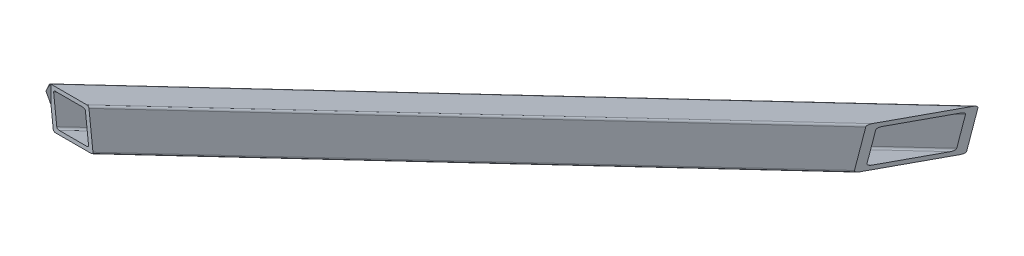
SolidWorks part; units mm, degrees
ref_plane "Plan de face" through (0, 0, 0) normal (0, 0, 1) x (1, 0, 0)
ref_plane "Plan de dessus" through (0, 0, 0) normal (0, 1, 0) x (1, 0, 0)
ref_plane "Plan de droite" through (0, 0, 0) normal (1, 0, 0) x (0, 0, -1)
sketch "Esquisse1" plane through (0, 0, 0) normal (0, 0, 1) x (1, 0, 0)
  line L0 (0, 0) -> (258, 0)
  line L1 (258, 0) -> (0, 256)
  line L2 (0, 256) -> (0, 0)
  dimension "D1" = 258
  dimension "D2" = 256
extrude "Boss.-Extru.1" add sketch "Esquisse1" along normal blind 729
sketch "Esquisse2" plane through (0, 0, 0) normal (-1, 0, 0) x (0, 0, 1)
  line L0 (0, 256) -> (729, 0)
  line L1 (729, 256) -> (0, 256) construction
  line L2 (0, 256) -> (0, 0) construction
  line L3 (729, 0) -> (729, 256)
  line L4 (729, 256) -> (0, 256)
extrude "Enlèv. mat.-Extru.1" cut sketch "Esquisse2" against normal blind 727
ref_plane "Plan1" through (0, 256, 0) normal (0.3167, -0.3143, 0.8949) x (0.9485, 0.1052, -0.2987)
sketch "Esquisse3" plane through (0, 256, 0) normal (0.3167, -0.3143, 0.8949) x (0.9485, 0.1052, -0.2987)
  line L1 (0, 0) -> (40, 0)
  line L2 (0, 0) -> (0, -40)
  line L3 (0, -40) -> (40, -40)
  line L4 (40, 0) -> (40, -40)
  dimension "D1" = 40
  dimension "D2" = 40
extrude "Boss.-Extru.2" add sketch "Esquisse3" along normal up to vertex (814.5803 mm away) up to point (258, 0, 729)
sketch "Esquisse4" plane through (0, 0, 0) normal (0, -1, 0) x (-1, 0, 0)
  line L1 (-258, -729) -> (-356.5784, -729)
  line L2 (-258, -729) -> (-258, -581.0499)
  line L3 (-258, -581.0499) -> (-356.5784, -581.0499)
  line L4 (-356.5784, -729) -> (-356.5784, -581.0499)
  line L5 (0, 0) -> (-77.8409, 0)
  line L6 (0, 0) -> (0, 46.0841)
  line L7 (0, 46.0841) -> (-77.8409, 46.0841)
  line L8 (-77.8409, 0) -> (-77.8409, 46.0841)
extrude "Enlèv. mat.-Extru.2" cut sketch "Esquisse4" against normal through all both and the other way through all
sketch "Esquisse7" plane through (0, 256, 0) normal (0.3167, -0.3143, 0.8949) x (0.9485, 0.1052, -0.2987)
  line L1 (40, 0) -> (0, 0)
  line L2 (40, 0) -> (40, -40)
  line L3 (40, -40) -> (0, -40)
  line L4 (0, 0) -> (0, -40)
  line L5 (433.6794, -362.0503) -> (-387.8651, -362.0503)
  line L6 (433.6794, -362.0503) -> (433.6794, 254.1081)
  line L7 (433.6794, 254.1081) -> (-387.8651, 254.1081)
  line L8 (-387.8651, -362.0503) -> (-387.8651, 254.1081)
extrude "Enlèv. mat.-Extru.6" cut sketch "Esquisse7" along normal through all
sketch "Esquisse8" plane through (0, 256, 0) normal (0.3167, -0.3143, 0.8949) x (0.9485, 0.1052, -0.2987)
  line L1 (0, 0) -> (40, 0) construction
  line L2 (0, 0) -> (0, -40) construction
  line L3 (0, -40) -> (40, -40) construction
  line L4 (40, 0) -> (40, -40) construction
  line L5 (40, 0) -> (40, -40) construction
  line L7 (4, -36) -> (36, -36)
  line L8 (36, -4) -> (36, -36)
  line L9 (4, -4) -> (36, -4)
  line L10 (4, -4) -> (4, -36)
  line L11 (40, -40) -> (0, -40) construction
  line L12 (0, -40) -> (0, 0) construction
  line L13 (40, -40) -> (0, -40) construction
  line L14 (0, 0) -> (40, 0) construction
  line L15 (40, 0) -> (40, -40) construction
  dimension "D1" = 4
extrude "Enlèv. mat.-Extru.9" cut sketch "Esquisse8" along normal through all
fillet "Congé2" radius 2 8 edges at (152.4359, 108.8711, 298.28) (150.0849, 148.933, 304.9229) (131.351, 87.9381, 357.8572) (131.3436, 126.0871, 357.878) (148.2115, 142.8335, 310.2163) (150.0923, 110.784, 304.902) (133.2244, 94.0376, 352.5637) (129, 128, 364.5)
mirror "Symétrie4" about plane through (0, 0, 0) normal (0, 0, 1) of bodies 108
sketch "Esquisse9" plane through (0, 0, 0) normal (0, 1, 0) x (1, 0, 0)
  line L1 (2.1085, 0) -> (400.5758, 0)
  line L2 (2.1085, 0) -> (2.1085, -786.4304)
  line L3 (2.1085, -786.4304) -> (400.5758, -786.4304)
  line L4 (400.5758, 0) -> (400.5758, -786.4304)
extrude "Enlèv. mat.-Extru.10" cut sketch "Esquisse9" against normal through all both and the other way through all
